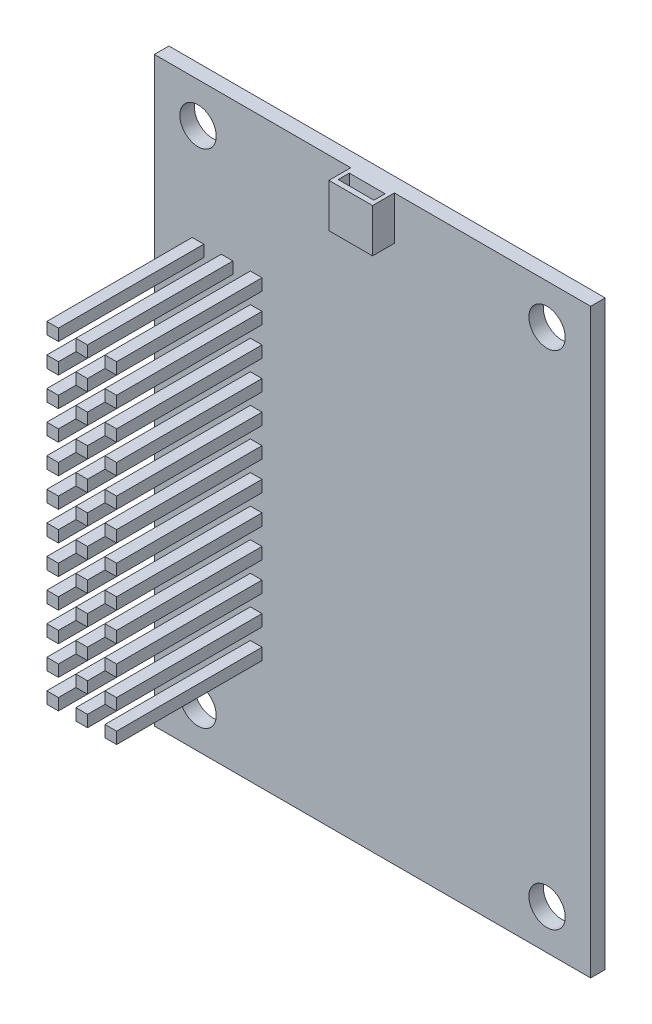
SolidWorks part; units mm, degrees
ref_plane "前视基准面" through (0, 0, 0) normal (0, 0, 1) x (1, 0, 0)
ref_plane "上视基准面" through (0, 0, 0) normal (0, 1, 0) x (1, 0, 0)
ref_plane "右视基准面" through (0, 0, 0) normal (1, 0, 0) x (0, 0, -1)
sketch "草图1" plane through (0, 0, 0) normal (0, 0, 1) x (1, 0, 0)
  line L0 (12, -16) -> (15, -20) construction
  line L1 (-15, -20) -> (15, -20)
  line L2 (-15, -20) -> (-15, 20)
  line L3 (-15, 20) -> (15, 20)
  line L4 (15, -20) -> (15, 20)
  line L5 (-12.75, -17) -> (-12, -16) construction
  line L6 (-15, 20) -> (0, 0) construction
  line L7 (-12, -16) -> (-10.75, -16) construction
  line L11 (0, 0) -> (10.503, 14.004) construction
  line L12 (-12, 16) -> (0, 0) construction
  line L13 (0, 0) -> (10.503, 14.004) construction
  line L15 (-12, -17.25) -> (12, -17.25) construction
  line L16 (-12, -17.25) -> (-12, 17.25) construction
  line L17 (-12, 17.25) -> (12, 17.25) construction
  line L18 (12, -17.25) -> (12, 17.25) construction
  line L19 (-12, -17.25) -> (12, 17.25) construction
  line L20 (-12, 17.25) -> (12, -17.25) construction
  circle A4 centre (-12, 17.25) radius 1.25
  circle A5 centre (12, 17.25) radius 1.25
  circle A6 centre (12, -17.25) radius 1.25
  circle A7 centre (-12, -17.25) radius 1.25
  point P0 (0, 0)
  point P5 (0, 0)
  dimension "D5" = 24
  dimension "D6" = 2.5
  dimension "D7" = 2.5
  dimension "D8" = 2.5
  dimension "D9" = 2.5
  dimension "D1" = 40
  dimension "D2" = 30
  dimension "D3" = 34.5
  dimension "D4" = 24
extrude "凸台-拉伸1" add sketch "草图1" along normal blind 1
sketch "草图2" plane through (0, 0, 1) normal (0, 0, 1) x (1, 0, 0)
  line L0 (-12, 16) -> (12, 16) construction
  line L1 (-12, 10.4) -> (-12, 7.6) construction
  line L2 (-12, -12.4) -> (-12, -12) construction
  line L3 (-12.4, -10.4) -> (-11.6, -10.4)
  line L4 (-12.4, -11.6) -> (-11.6, -11.6)
  line L5 (-12.4, -11.6) -> (-12.4, -12.4)
  line L6 (-12.4, -12.4) -> (-11.6, -12.4)
  line L7 (-11.6, -11.6) -> (-11.6, -12.4)
  line L8 (-12.4, -11.6) -> (-11.6, -12.4) construction
  line L9 (-12.4, -12.4) -> (-11.6, -11.6) construction
  line L10 (-11.6, -9.6) -> (-11.6, -10.4)
  line L11 (-12.4, -9.6) -> (-11.6, -9.6)
  line L12 (-12.4, -9.6) -> (-12.4, -10.4)
  line L13 (-12.4, -8.4) -> (-11.6, -8.4)
  line L14 (-11.6, -7.6) -> (-11.6, -8.4)
  line L15 (-12.4, -7.6) -> (-11.6, -7.6)
  line L16 (-12.4, -7.6) -> (-12.4, -8.4)
  line L17 (-12.4, -6.4) -> (-11.6, -6.4)
  line L18 (-11.6, -5.6) -> (-11.6, -6.4)
  line L19 (-12.4, -5.6) -> (-11.6, -5.6)
  line L20 (-12.4, -5.6) -> (-12.4, -6.4)
  line L21 (-12.4, -4.4) -> (-11.6, -4.4)
  line L22 (-11.6, -3.6) -> (-11.6, -4.4)
  line L23 (-12.4, -3.6) -> (-11.6, -3.6)
  line L24 (-12.4, -3.6) -> (-12.4, -4.4)
  line L25 (-12.4, -2.4) -> (-11.6, -2.4)
  line L26 (-11.6, -1.6) -> (-11.6, -2.4)
  line L27 (-12.4, -1.6) -> (-11.6, -1.6)
  line L28 (-12.4, -1.6) -> (-12.4, -2.4)
  line L29 (-12.4, -0.4) -> (-11.6, -0.4)
  line L30 (-11.6, 0.4) -> (-11.6, -0.4)
  line L31 (-12.4, 0.4) -> (-11.6, 0.4)
  line L32 (-12.4, 0.4) -> (-12.4, -0.4)
  line L33 (-12.4, 1.6) -> (-11.6, 1.6)
  line L34 (-11.6, 2.4) -> (-11.6, 1.6)
  line L35 (-12.4, 2.4) -> (-11.6, 2.4)
  line L36 (-12.4, 2.4) -> (-12.4, 1.6)
  line L37 (-12.4, 3.6) -> (-11.6, 3.6)
  line L38 (-11.6, 4.4) -> (-11.6, 3.6)
  line L39 (-12.4, 4.4) -> (-11.6, 4.4)
  line L40 (-12.4, 4.4) -> (-12.4, 3.6)
  line L41 (-12.4, 5.6) -> (-11.6, 5.6)
  line L42 (-11.6, 6.4) -> (-11.6, 5.6)
  line L43 (-12.4, 6.4) -> (-11.6, 6.4)
  line L44 (-12.4, 6.4) -> (-12.4, 5.6)
  line L45 (-12.4, 7.6) -> (-11.6, 7.6)
  line L46 (-11.6, 8.4) -> (-11.6, 7.6)
  line L47 (-12.4, 8.4) -> (-11.6, 8.4)
  line L48 (-12.4, 8.4) -> (-12.4, 7.6)
  line L49 (-12.4, 9.6) -> (-11.6, 9.6)
  line L50 (-11.6, 10.4) -> (-11.6, 9.6)
  line L51 (-12.4, 10.4) -> (-11.6, 10.4)
  line L52 (-12.4, 10.4) -> (-12.4, 9.6)
  line L53 (-10.4, -10.4) -> (-9.6, -10.4)
  line L54 (-10.4, -11.6) -> (-9.6, -11.6)
  line L55 (-10.4, -11.6) -> (-10.4, -12.4)
  line L56 (-10.4, -12.4) -> (-9.6, -12.4)
  line L57 (-9.6, -11.6) -> (-9.6, -12.4)
  line L58 (-9.6, -9.6) -> (-9.6, -10.4)
  line L59 (-10.4, -9.6) -> (-9.6, -9.6)
  line L60 (-10.4, -9.6) -> (-10.4, -10.4)
  line L61 (-10.4, -8.4) -> (-9.6, -8.4)
  line L62 (-9.6, -7.6) -> (-9.6, -8.4)
  line L63 (-10.4, -7.6) -> (-9.6, -7.6)
  line L64 (-10.4, -7.6) -> (-10.4, -8.4)
  line L65 (-10.4, -6.4) -> (-9.6, -6.4)
  line L66 (-9.6, -5.6) -> (-9.6, -6.4)
  line L67 (-10.4, -5.6) -> (-9.6, -5.6)
  line L68 (-10.4, -5.6) -> (-10.4, -6.4)
  line L69 (-10.4, -4.4) -> (-9.6, -4.4)
  line L70 (-9.6, -3.6) -> (-9.6, -4.4)
  line L71 (-10.4, -3.6) -> (-9.6, -3.6)
  line L72 (-10.4, -3.6) -> (-10.4, -4.4)
  line L73 (-10.4, -2.4) -> (-9.6, -2.4)
  line L74 (-9.6, -1.6) -> (-9.6, -2.4)
  line L75 (-10.4, -1.6) -> (-9.6, -1.6)
  line L76 (-10.4, -1.6) -> (-10.4, -2.4)
  line L77 (-10.4, -0.4) -> (-9.6, -0.4)
  line L78 (-9.6, 0.4) -> (-9.6, -0.4)
  line L79 (-10.4, 0.4) -> (-9.6, 0.4)
  line L80 (-10.4, 0.4) -> (-10.4, -0.4)
  line L81 (-10.4, 1.6) -> (-9.6, 1.6)
  line L82 (-9.6, 2.4) -> (-9.6, 1.6)
  line L83 (-10.4, 2.4) -> (-9.6, 2.4)
  line L84 (-10.4, 2.4) -> (-10.4, 1.6)
  line L85 (-10.4, 3.6) -> (-9.6, 3.6)
  line L86 (-9.6, 4.4) -> (-9.6, 3.6)
  line L87 (-10.4, 4.4) -> (-9.6, 4.4)
  line L88 (-10.4, 4.4) -> (-10.4, 3.6)
  line L89 (-10.4, 5.6) -> (-9.6, 5.6)
  line L90 (-9.6, 6.4) -> (-9.6, 5.6)
  line L91 (-10.4, 6.4) -> (-9.6, 6.4)
  line L92 (-10.4, 6.4) -> (-10.4, 5.6)
  line L93 (-10.4, 7.6) -> (-9.6, 7.6)
  line L94 (-9.6, 8.4) -> (-9.6, 7.6)
  line L95 (-10.4, 8.4) -> (-9.6, 8.4)
  line L96 (-10.4, 8.4) -> (-10.4, 7.6)
  line L97 (-10.4, 9.6) -> (-9.6, 9.6)
  line L98 (-9.6, 10.4) -> (-9.6, 9.6)
  line L99 (-10.4, 10.4) -> (-9.6, 10.4)
  line L100 (-10.4, 10.4) -> (-10.4, 9.6)
  line L101 (-10, 10.4) -> (-10, -16) construction
  line L102 (-10, -16) -> (-10, -12) construction
  line L103 (-10.4, -11.6) -> (-9.6, -12.4) construction
  line L104 (-10.4, -12.4) -> (-9.6, -11.6) construction
  line L105 (-8.4, -10.4) -> (-7.6, -10.4)
  line L106 (-8.4, -11.6) -> (-7.6, -11.6)
  line L107 (-8.4, -11.6) -> (-8.4, -12.4)
  line L108 (-8.4, -12.4) -> (-7.6, -12.4)
  line L109 (-7.6, -11.6) -> (-7.6, -12.4)
  line L110 (-7.6, -9.6) -> (-7.6, -10.4)
  line L111 (-8.4, -9.6) -> (-7.6, -9.6)
  line L112 (-8.4, -9.6) -> (-8.4, -10.4)
  line L113 (-8.4, -8.4) -> (-7.6, -8.4)
  line L114 (-7.6, -7.6) -> (-7.6, -8.4)
  line L115 (-8.4, -7.6) -> (-7.6, -7.6)
  line L116 (-8.4, -7.6) -> (-8.4, -8.4)
  line L117 (-8.4, -6.4) -> (-7.6, -6.4)
  line L118 (-7.6, -5.6) -> (-7.6, -6.4)
  line L119 (-8.4, -5.6) -> (-7.6, -5.6)
  line L120 (-8.4, -5.6) -> (-8.4, -6.4)
  line L121 (-8.4, -4.4) -> (-7.6, -4.4)
  line L122 (-7.6, -3.6) -> (-7.6, -4.4)
  line L123 (-8.4, -3.6) -> (-7.6, -3.6)
  line L124 (-8.4, -3.6) -> (-8.4, -4.4)
  line L125 (-8.4, -2.4) -> (-7.6, -2.4)
  line L126 (-7.6, -1.6) -> (-7.6, -2.4)
  line L127 (-8.4, -1.6) -> (-7.6, -1.6)
  line L128 (-8.4, -1.6) -> (-8.4, -2.4)
  line L129 (-8.4, -0.4) -> (-7.6, -0.4)
  line L130 (-7.6, 0.4) -> (-7.6, -0.4)
  line L131 (-8.4, 0.4) -> (-7.6, 0.4)
  line L132 (-8.4, 0.4) -> (-8.4, -0.4)
  line L133 (-8.4, 1.6) -> (-7.6, 1.6)
  line L134 (-7.6, 2.4) -> (-7.6, 1.6)
  line L135 (-8.4, 2.4) -> (-7.6, 2.4)
  line L136 (-8.4, 2.4) -> (-8.4, 1.6)
  line L137 (-8.4, 3.6) -> (-7.6, 3.6)
  line L138 (-7.6, 4.4) -> (-7.6, 3.6)
  line L139 (-8.4, 4.4) -> (-7.6, 4.4)
  line L140 (-8.4, 4.4) -> (-8.4, 3.6)
  line L141 (-8.4, 5.6) -> (-7.6, 5.6)
  line L142 (-7.6, 6.4) -> (-7.6, 5.6)
  line L143 (-8.4, 6.4) -> (-7.6, 6.4)
  line L144 (-8.4, 6.4) -> (-8.4, 5.6)
  line L145 (-8.4, 7.6) -> (-7.6, 7.6)
  line L146 (-7.6, 8.4) -> (-7.6, 7.6)
  line L147 (-8.4, 8.4) -> (-7.6, 8.4)
  line L148 (-8.4, 8.4) -> (-8.4, 7.6)
  line L149 (-8.4, 9.6) -> (-7.6, 9.6)
  line L150 (-7.6, 10.4) -> (-7.6, 9.6)
  line L151 (-8.4, 10.4) -> (-7.6, 10.4)
  line L152 (-8.4, 10.4) -> (-8.4, 9.6)
  line L153 (-8, 10.4) -> (-8, -16) construction
  line L154 (-8, -16) -> (-8, -12) construction
  line L155 (-8.4, -11.6) -> (-7.6, -12.4) construction
  line L156 (-8.4, -12.4) -> (-7.6, -11.6) construction
  line L157 (-12, 6.4) -> (-12, -12.4) construction
  dimension "D2" = 0.8
  dimension "D3" = 12
  dimension "D4" = 3
extrude "凸台-拉伸2" add sketch "草图2" along normal blind 10
sketch "草图3" plane through (0, 20, 0) normal (0, 1, 0) x (1, 0, 0)
  line L0 (0, -1) -> (-1.5, -1) construction
  line L1 (15, -1) -> (-15, -1) construction
  line L3 (-1.5, -1) -> (1.5, -1)
  line L4 (-1.5, -1) -> (-1.5, -2.5)
  line L5 (-1.5, -2.5) -> (1.5, -2.5)
  line L6 (1.5, -1) -> (1.5, -2.5)
  dimension "D1" = 1.5
  dimension "D2" = 1.5
  dimension "D3" = 3
extrude "凸台-拉伸3" add sketch "草图3" against normal blind 3
sketch "草图4" plane through (0, 20, 0) normal (0, 1, 0) x (1, 0, 0)
  line L0 (0, -2.5) -> (0, -1) construction
  line L1 (-1.5, -2.5) -> (1.5, -2.5) construction
  line L3 (-1.2311, -2.1333) -> (1.2311, -2.1333)
  line L4 (-1.2311, -2.1333) -> (-1.2311, -1.3667)
  line L5 (-1.2311, -1.3667) -> (1.2311, -1.3667)
  line L6 (1.2311, -2.1333) -> (1.2311, -1.3667)
  line L7 (-1.2311, -2.1333) -> (1.2311, -1.3667) construction
  line L8 (-1.2311, -1.3667) -> (1.2311, -2.1333) construction
  point P5 (0, -1.75)
  dimension "D1" = 1.5
extrude "切除-拉伸1" cut sketch "草图4" against normal blind 1.5
